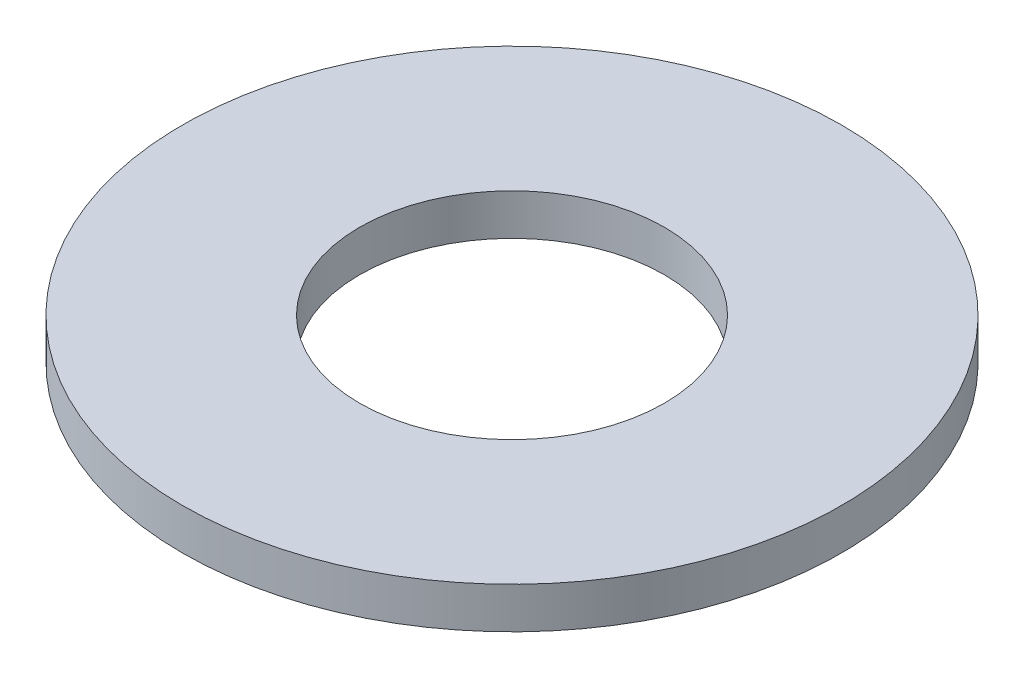
SolidWorks part; units mm, degrees
material "Plain Carbon Steel"
ref_plane "Front Plane" through (0, 0, 0) normal (0, 0, 1) x (1, 0, 0)
ref_plane "Top Plane" through (0, 0, 0) normal (0, 1, 0) x (1, 0, 0)
ref_plane "Right Plane" through (0, 0, 0) normal (1, 0, 0) x (0, 0, -1)
sketch "Sketch1" plane through (0, 0, 0) normal (0, 1, 0) x (1, 0, 0)
  circle A0 centre (0, 0) radius 1.85
  circle A1 centre (0, 0) radius 4
  dimension "Washer_ID" = 3.7
  dimension "Washer_OD" = 8
extrude "Washer_Body" add sketch "Sketch1" along normal blind 0.5
